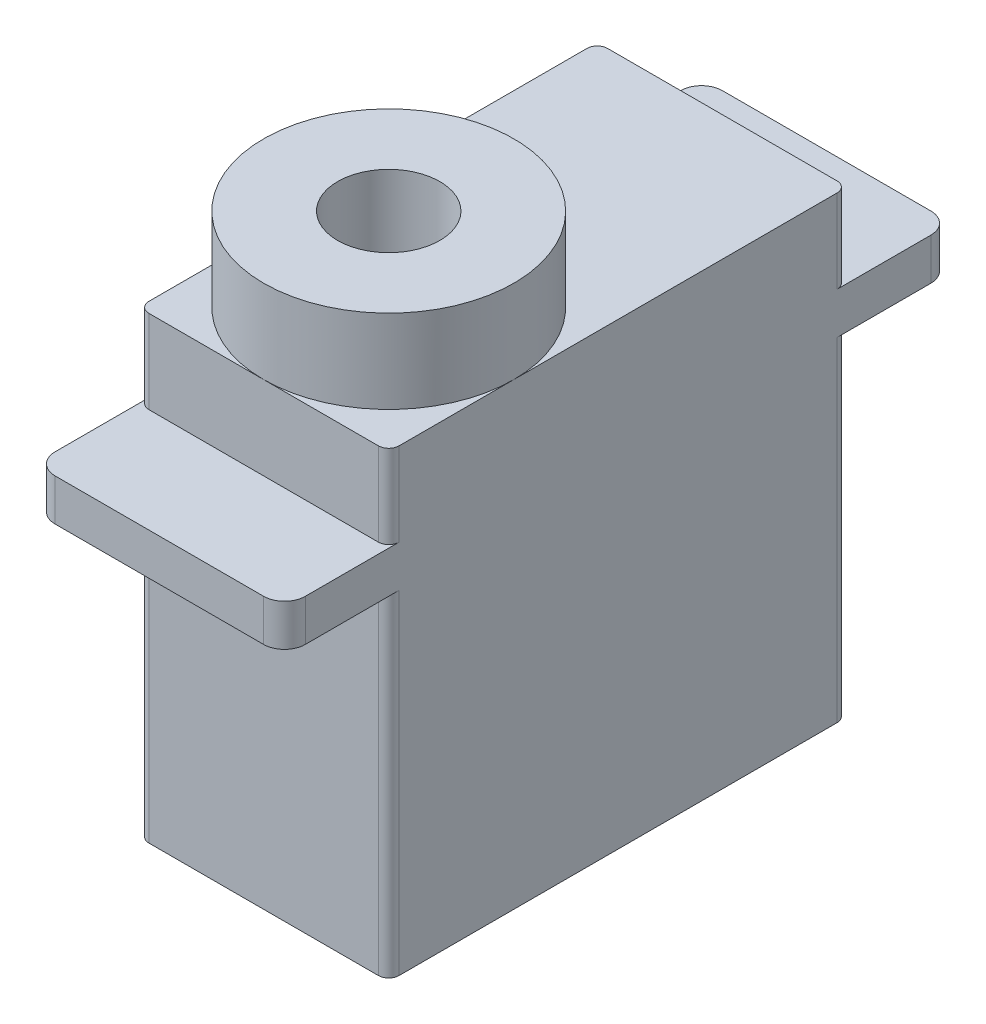
SolidWorks part; units mm, degrees
material "Polyester Resin"
ref_plane "Front Plane" through (0, 0, 0) normal (0, 0, 1) x (1, 0, 0)
ref_plane "Top Plane" through (0, 0, 0) normal (0, 1, 0) x (1, 0, 0)
ref_plane "Right Plane" through (0, 0, 0) normal (1, 0, 0) x (0, 0, -1)
sketch "Sketch2" plane through (0, 0, 0) normal (0, 1, 0) x (1, 0, 0)
  line L1 (0, -31.7209) -> (12, -31.7209)
  line L2 (0, -31.7209) -> (0, -53.7209)
  line L3 (0, -53.7209) -> (12, -53.7209)
  line L4 (12, -31.7209) -> (12, -53.7209)
  dimension "D1" = 12
  dimension "D2" = 22
extrude "Boss-Extrude1" add sketch "Sketch2" along normal blind 22
sketch "Sketch3" plane through (0, 22, 0) normal (0, 1, 0) x (1, 0, 0)
  line L0 (0, -53.7209) -> (12, -53.7209) construction
  line L1 (12, -53.7209) -> (12, -31.7209) construction
  circle A0 centre (6, -47.7209) radius 6
  circle A1 centre (6, -47.7209) radius 2.45
  point P7 (0, 0)
  dimension "D3" = 12
  dimension "D4" = 4.9
  dimension "D1" = 6
  dimension "D2" = 6
extrude "Boss-Extrude2" add sketch "Sketch3" along normal blind 4
sketch "Sketch4" plane through (0, 0, 53.7209) normal (0, 0, 1) x (1, 0, 0)
  line L0 (6, 22) -> (0, 22) construction
  line L1 (0, 18) -> (12, 18)
  line L2 (0, 18) -> (0, 16)
  line L3 (0, 16) -> (12, 16)
  line L4 (12, 18) -> (12, 16)
  dimension "D1" = 4
  dimension "D2" = 2
extrude "Boss-Extrude3" add sketch "Sketch4" along normal blind 5
sketch "Sketch5" plane through (0, 0, 31.7209) normal (0, 0, -1) x (-1, 0, 0)
  line L1 (-12, 22) -> (0, 22) construction
  line L2 (-12, 18) -> (0, 18)
  line L3 (-12, 18) -> (-12, 16)
  line L4 (-12, 16) -> (0, 16)
  line L5 (0, 18) -> (0, 16)
  dimension "D1" = 4
  dimension "D2" = 2
extrude "Boss-Extrude4" add sketch "Sketch5" along normal blind 5
fillet "Fillet1" radius 1 4 edges at (0, 17, 26.7209) (12, 17, 26.7209) (0, 17, 58.7209) (12, 17, 58.7209)
fillet "Fillet2" radius 0.5 8 edges at (12, 20, 53.7209) (0, 20, 53.7209) (0, 20, 31.7209) (12, 20, 31.7209) (12, 8, 31.7209) (0, 8, 31.7209) (0, 8, 53.7209) (12, 8, 53.7209)
